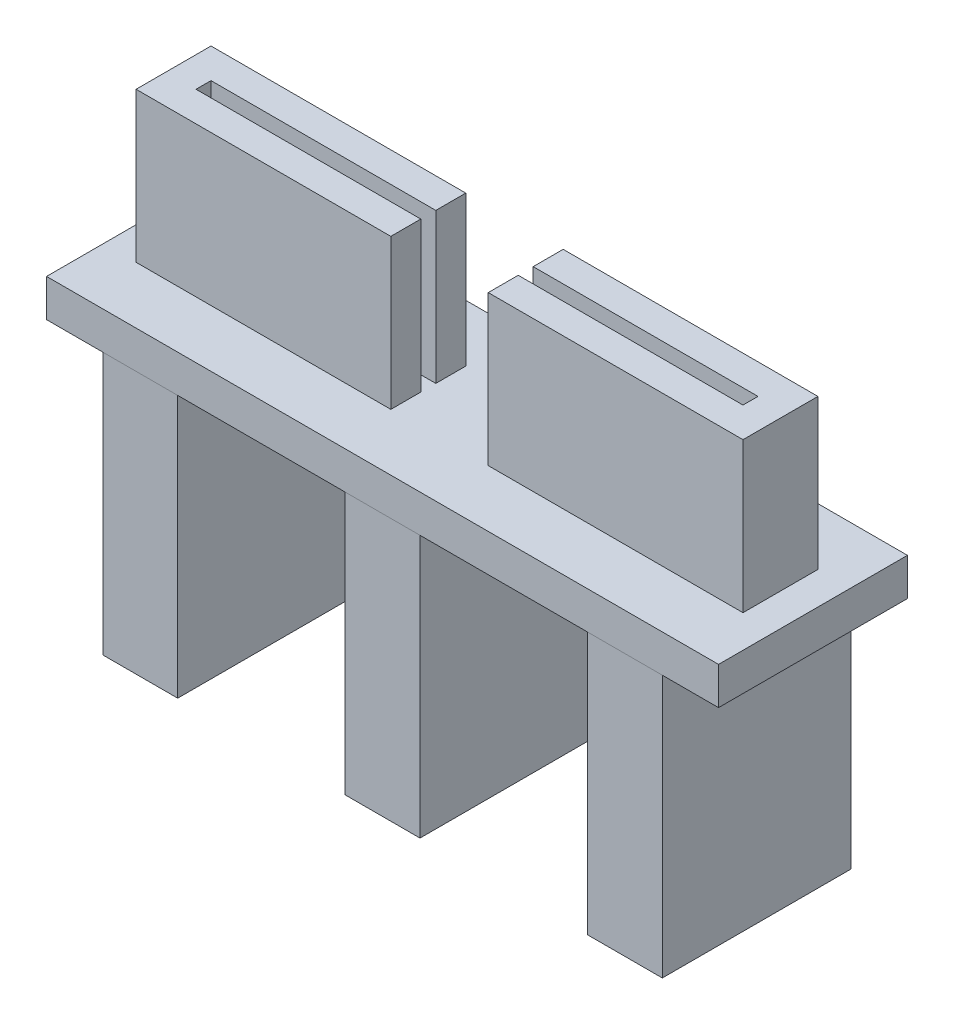
SolidWorks part; units mm, degrees
ref_plane "Front Plane" through (0, 0, 0) normal (0, 0, 1) x (1, 0, 0)
ref_plane "Top Plane" through (0, 0, 0) normal (0, 1, 0) x (1, 0, 0)
ref_plane "Right Plane" through (0, 0, 0) normal (1, 0, 0) x (0, 0, -1)
sketch "Sketch1" plane through (0, 0, 0) normal (0, 1, 0) x (1, 0, 0)
  line L1 (-70, -50) -> (70, -50)
  line L2 (-70, -50) -> (-70, 50)
  line L3 (-70, 50) -> (70, 50)
  line L4 (70, -50) -> (70, 50)
  line L5 (-70, -50) -> (70, 50) construction
  line L6 (-70, 50) -> (70, -50) construction
  point P0 (0, 0)
  point P6 (0, 0)
  dimension "D1" = 140
  dimension "D2" = 100
extrude "Boss-Extrude2" add sketch "Sketch1" along normal blind 40 draft 20
shell "Shell1" thickness 5
sketch "Sketch4" plane through (0, 0, 0) normal (0, -1, 0) x (1, 0, 0)
  line L0 (-64.6791, 44.6791) -> (64.6791, 44.6791) construction
  line L1 (0, 44.6791) -> (-64.6791, 44.6791) construction
  line L2 (-32.3396, 44.6791) -> (-32.3396, -44.6791) construction
  line L3 (64.6791, -44.6791) -> (-64.6791, -44.6791) construction
  line L4 (0, 44.6791) -> (0, -44.6791) construction
  line L5 (-27.3396, 44.6791) -> (-37.3396, 44.6791)
  line L6 (-37.3396, 44.6791) -> (-37.3396, -44.6791)
  line L7 (-27.3396, -44.6791) -> (-27.3396, 44.6791)
  line L8 (27.3396, -44.6791) -> (27.3396, 44.6791)
  line L9 (37.3396, 44.6791) -> (37.3396, -44.6791)
  line L10 (-32.3396, 44.6791) -> (0, 44.6791) construction
  line L11 (-16.1698, 44.6791) -> (-16.1698, -44.6791) construction
  line L12 (-5, -44.6791) -> (-5, 44.6791)
  line L13 (5, 44.6791) -> (5, -44.6791)
  point P13 (-32.3396, 44.6791)
  line M10 (-64.6791, 44.6791) -> (64.6791, 44.6791)
  line M12 (64.6791, -44.6791) -> (-64.6791, -44.6791)
  dimension "D1" = 10
extrude "Boss-Extrude3" add sketch "Sketch4" against normal up to body separate body contours L7 L6 M12 M10 | L9 L8 M10 M12 | L13 L12 M10 M12
sketch "Sketch8" plane through (0, 0, 0) normal (0, -1, 0) x (1, 0, 0)
  line L0 (-37.3396, 44.6791) -> (-37.3396, 50) construction
  line L1 (-70, 50) -> (70, 50) construction
  line L2 (0, 50) -> (0, -50) construction
  line L3 (-37.3396, 50) -> (-27.3396, 50)
  line L4 (-37.3396, 50) -> (-37.3396, 40)
  line L5 (-37.3396, 40) -> (-27.3396, 40)
  line L6 (-27.3396, 50) -> (-27.3396, 40)
  line L7 (70, -50) -> (-70, -50) construction
  line L8 (37.3396, 40) -> (27.3396, 40)
  line L9 (27.3396, 50) -> (27.3396, 40)
  line L10 (37.3396, 50) -> (27.3396, 50)
  line L11 (37.3396, 50) -> (37.3396, 40)
  dimension "D1" = 10
  dimension "D2" = 10
extrude "Boss-Extrude4" add sketch "Sketch8" along normal blind 30 separate body
sketch "Sketch9" plane through (37.3396, 0, 0) normal (1, 0, 0) x (0, 0, -1)
  line L0 (-40, -15) -> (-25, 0)
  line L1 (-40, -30) -> (-40, 0) construction
  line L3 (-40, -10) -> (-30, 0)
  line L4 (-50, 0) -> (50, 0) construction
  line L5 (-30, 0) -> (-25, 0)
  line L6 (-40, -10) -> (-40, -15)
  dimension "D1" = 45
  dimension "D2" = 5
  dimension "D3" = 5
extrude "Boss-Extrude5" add sketch "Sketch9" against normal up to surface (74.6791 mm away) up to face at (-37.3396, 17.5, 0)
sketch "Sketch12" plane through (0, 40, 0) normal (0, 1, 0) x (1, 0, 0)
  line L0 (36.5, 0) -> (-36.5, 0) construction
  line L1 (-36.5, -1) -> (-36.5, 1)
  line L2 (-36.5, 1) -> (-6.5, 1)
  line L3 (-36.5, -1) -> (-6.5, -1)
  line L4 (0, -35.4412) -> (0, 35.4412) construction
  line L5 (55.4412, 35.4412) -> (-55.4412, 35.4412) construction
  line L6 (-6.5, 1) -> (-6.5, 5)
  line L7 (-6.5, 5) -> (-34.4333, 5)
  line L8 (-6.5, -1) -> (-6.5, -5)
  line L9 (-6.5, -5) -> (-36.5, -5)
  line L10 (-34.4333, 5) -> (-40.5, 5)
  line L11 (-40.5, 5) -> (-40.5, -5)
  line L12 (-40.5, -5) -> (-36.5, -5)
  line L13 (40.5, 5) -> (40.5, -5)
  line L14 (34.4333, 5) -> (40.5, 5)
  line L15 (6.5, 5) -> (34.4333, 5)
  line L16 (6.5, 1) -> (6.5, 5)
  line L17 (36.5, 1) -> (6.5, 1)
  line L18 (36.5, -1) -> (36.5, 1)
  line L19 (36.5, -1) -> (6.5, -1)
  line L20 (6.5, -1) -> (6.5, -5)
  line L21 (6.5, -5) -> (36.5, -5)
  line L22 (40.5, -5) -> (36.5, -5)
  point P4 (0, 0)
  point P7 (-36.5, 0)
  point P14 (0, 0)
  dimension "D1" = 73
  dimension "D2" = 2
  dimension "D3" = 30
  dimension "D4" = 30
  dimension "D5" = 4
  dimension "D6" = 4
  dimension "D7" = 6.0667
  dimension "D8" = 4
extrude "Boss-Extrude6" add sketch "Sketch12" along normal blind 20
sketch "Sketch13" plane through (0, 0, 40) normal (0, 0, -1) x (-1, 0, 0)
  line L0 (-32.3396, -15) -> (-32.3396, -30) construction
  line L1 (-27.3396, -15) -> (-37.3396, -15) construction
  line L2 (-27.3396, -30) -> (-37.3396, -30) construction
  line L3 (-37.3396, -22.5) -> (-27.3396, -22.5) construction
  line L4 (-37.3396, -30) -> (-37.3396, -15) construction
  line L5 (-27.3396, -30) -> (-27.3396, -15) construction
  line L6 (0, -60) -> (0, 60) construction
  circle A0 centre (-32.3396, -22.5) radius 3.25
  circle A1 centre (32.3396, -22.5) radius 3.25
  point P18 (0, 0)
  dimension "D1" = 6.5
extrude "Cut-Extrude2" cut sketch "Sketch13" against normal through all
sketch "Sketch14" plane through (0, 40, 0) normal (0, 1, 0) x (1, 0, 0)
  line L0 (0, 35.4412) -> (0, -35.4412) construction
  line L1 (55.4412, 35.4412) -> (-55.4412, 35.4412) construction
  line L2 (-55.4412, -35.4412) -> (55.4412, -35.4412) construction
  line L3 (-55.4412, 35.4412) -> (-55.4412, -35.4412) construction
  line L4 (55.4412, -35.4412) -> (55.4412, 35.4412) construction
  circle A0 centre (0, -23.6312) radius 3.25
  circle A1 centre (27.7212, 23.6312) radius 3.25
  circle A2 centre (-27.7212, 23.6312) radius 3.25
  dimension "D1" = 6.5
  dimension "D5" = 6.5
  dimension "D6" = 6.5
  dimension "D2" = 11.81
  dimension "D3" = 11.81
  dimension "D4" = 11.81
  dimension "D7" = 27.72
  dimension "D8" = 27.72
extrude "Cut-Extrude3" cut sketch "Sketch14" against normal through all contours A2 | A1 | L0 A0
sketch "Sketch15" plane through (0, 40, 0) normal (0, 1, 0) x (1, 0, 0)
  line L1 (-44.8422, -12.6054) -> (44.8422, -12.6054)
  line L2 (-44.8422, -12.6054) -> (-44.8422, 12.6054)
  line L3 (-44.8422, 12.6054) -> (44.8422, 12.6054)
  line L4 (44.8422, -12.6054) -> (44.8422, 12.6054)
  line L5 (-44.8422, -12.6054) -> (44.8422, 12.6054) construction
  line L6 (-44.8422, 12.6054) -> (44.8422, -12.6054) construction
  point P0 (0, 0)
  dimension "D1" = 89.6844
  dimension "D2" = 25.2108
extrude "Cut-Extrude6" cut sketch "Sketch15" against normal through all flip side to cut
